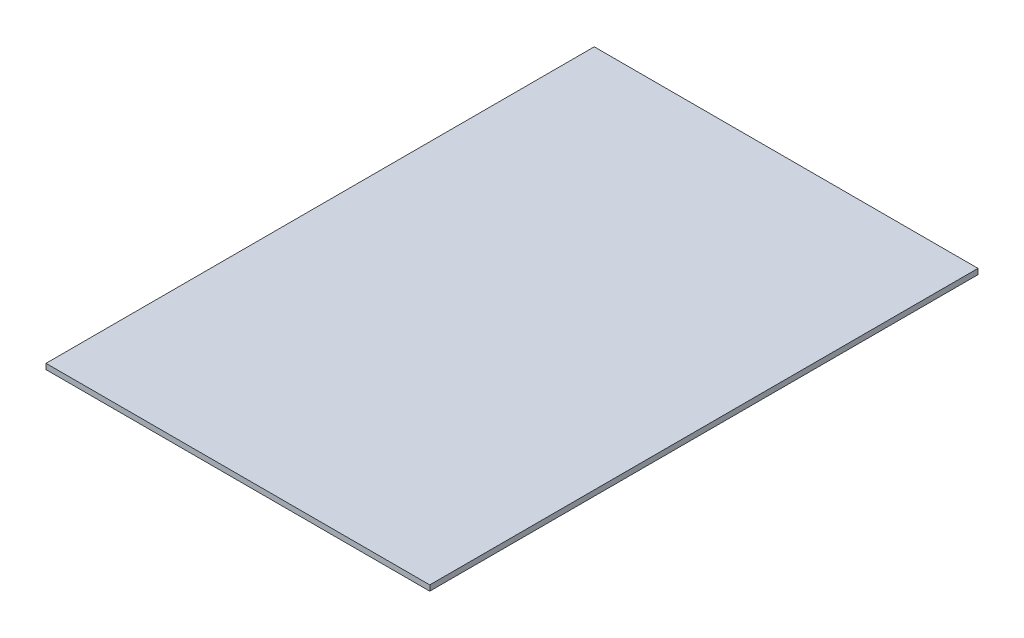
SolidWorks part; units mm, degrees
ref_plane "Front Plane" through (0, 0, 0) normal (0, 0, 1) x (1, 0, 0)
ref_plane "Top Plane" through (0, 0, 0) normal (0, 1, 0) x (1, 0, 0)
ref_plane "Right Plane" through (0, 0, 0) normal (1, 0, 0) x (0, 0, -1)
sketch "Sketch1" plane through (0, 0, 0) normal (0, 1, 0) x (1, 0, 0)
  line L1 (1750, -2500) -> (-1750, -2500)
  line L2 (1750, -2500) -> (1750, 2500)
  line L3 (1750, 2500) -> (-1750, 2500)
  line L4 (-1750, -2500) -> (-1750, 2500)
  line L5 (1750, -2500) -> (-1750, 2500) construction
  line L6 (1750, 2500) -> (-1750, -2500) construction
  point P0 (0, 0)
  dimension "D1" = 3500
  dimension "D2" = 5000
extrude "Boss-Extrude1" add sketch "Sketch1" along normal blind 50
sketch "Sketch2" plane through (0, 0, 0) normal (0, -1, 0) x (1, 0, 0)
  line L0 (1750, -2500) -> (-1750, -2500) construction
  line L2 (-1750, 2500) -> (-1750, -2500)
  line L3 (-1750, -2500) -> (-1700, -2500)
  line L4 (-1700, 2500) -> (-1700, -2500)
  line L5 (-1750, 2500) -> (-1700, -2500) construction
  line L6 (-1750, -2500) -> (-1700, 2500) construction
  line L7 (-1750, 2500) -> (1750, 2500) construction
  line L9 (1750, 2500) -> (1750, -2500)
  line L10 (1750, -2500) -> (1700, -2500)
  line L11 (1700, 2500) -> (1700, -2500)
  line L12 (1750, 2500) -> (1700, -2500) construction
  line L13 (1750, -2500) -> (1700, 2500) construction
  line L14 (25, -2500) -> (-25, -2500)
  line L15 (25, -2500) -> (25, 2500)
  line L17 (-25, -2500) -> (-25, 2500)
  line L18 (25, -2500) -> (-25, 2500) construction
  line L19 (25, 2500) -> (-25, -2500) construction
  line L20 (-1750, 1500) -> (1750, 1500) construction
  line L21 (-1750, 2500) -> (1750, 2500)
  line L23 (-1750, 2450) -> (1750, 2450)
  line L25 (-1750, 2500) -> (1750, 2450) construction
  line L26 (-1750, 2450) -> (1750, 2500) construction
  line L29 (862.5, 2500) -> (862.5, 347.637) construction
  line L31 (-862.5, 2500) -> (-862.5, 253.9485) construction
  line L33 (-487.5, 1125) -> (-1237.5, 1125)
  line L34 (-487.5, 1125) -> (-487.5, 1875)
  line L35 (-487.5, 1875) -> (-1237.5, 1875)
  line L36 (-1237.5, 1125) -> (-1237.5, 1875)
  line L37 (-487.5, 1125) -> (-1237.5, 1875) construction
  line L38 (-487.5, 1875) -> (-1237.5, 1125) construction
  line L39 (1237.5, 1125) -> (487.5, 1125)
  line L40 (1237.5, 1125) -> (1237.5, 1875)
  line L41 (1237.5, 1875) -> (487.5, 1875)
  line L42 (487.5, 1125) -> (487.5, 1875)
  line L43 (1237.5, 1125) -> (487.5, 1875) construction
  line L44 (1237.5, 1875) -> (487.5, 1125) construction
  point P4 (-1725, 0)
  point P12 (1725, 0)
  point P14 (0, 0)
  point P24 (0, 2475)
  point P31 (-862.5, 1500)
  point P36 (862.5, 1500)
  dimension "D1" = 50
  dimension "D2" = 50
  dimension "D3" = 50
  dimension "D4" = 50
  dimension "D5" = 1000
  dimension "D6" = 750
  dimension "D7" = 750
extrude "Cut-Extrude1" cut sketch "Sketch2" against normal blind 10 contours L36 L33 L34 L35 | L42 L39 L40 L41
sketch "Sketch3" plane through (0, 0, 0) normal (0, -1, 0) x (1, 0, 0)
  line L0 (1750, -1500) -> (-1750, -1500) construction
  line L1 (1750, 2500) -> (1750, -2500) construction
  line L2 (-1750, -2500) -> (-1750, 2500) construction
  line L3 (1750, -2500) -> (-1750, -2500) construction
  line L5 (375, -1875) -> (-375, -1875)
  line L6 (375, -1875) -> (375, -1125)
  line L7 (375, -1125) -> (-375, -1125)
  line L8 (-375, -1875) -> (-375, -1125)
  line L9 (375, -1875) -> (-375, -1125) construction
  line L10 (375, -1125) -> (-375, -1875) construction
  point P8 (0, -1500)
  dimension "D1" = 1000
  dimension "D2" = 750
  dimension "D3" = 750
extrude "Cut-Extrude2" cut sketch "Sketch3" against normal blind 10
